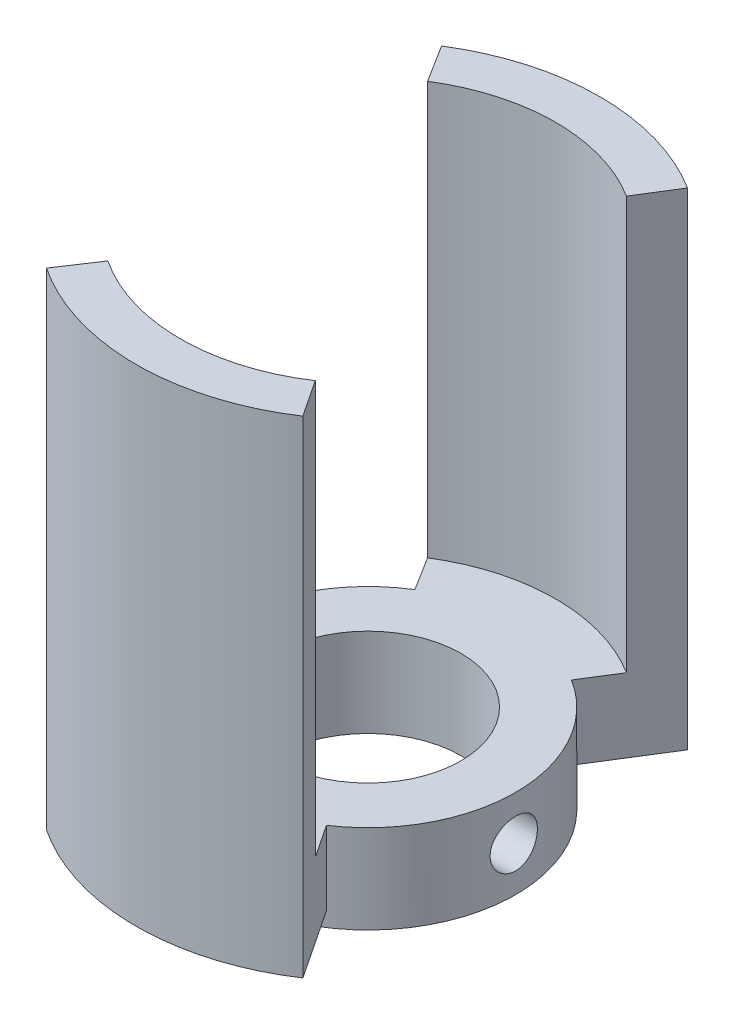
SolidWorks part; units mm, degrees
material "Plain Carbon Steel"
ref_plane "Front Plane" through (0, 0, 0) normal (0, 0, 1) x (1, 0, 0)
ref_plane "Top Plane" through (0, 0, 0) normal (0, 1, 0) x (1, 0, 0)
ref_plane "Right Plane" through (0, 0, 0) normal (1, 0, 0) x (0, 0, -1)
sketch "Sketch1" plane through (0, 0, 0) normal (0, 0, 1) x (1, 0, 0)
  line L0 (0, 5.8882) -> (0, -5.8882) construction
  line L7 (0, 0) -> (0, -3)
  line L9 (-5, -3) -> (0, -3)
  line L12 (-5, -3) -> (-5, 0)
  line L13 (-5, 0) -> (0, 0)
  dimension "D4" = 5
revolve "Revolve1" add sketch "Sketch1" angle 360 about L0
sketch "Sketch2" plane through (0, 0, 0) normal (0, 1, 0) x (1, 0, 0)
  circle A0 centre (0, 0) radius 3.15
  dimension "D1" = 6.3
extrude "Cut-Extrude1" cut sketch "Sketch2" against normal through all
ref_plane "Plane1" through (5, 0, 0) normal (1, 0, 0) x (0, 0, -1)
hole_wizard "M2x0.4 Tapped Hole2" positions "Sketch7" profile "Sketch8" tap size "M2x0.4" standard "ANSI Metric"
sketch "Sketch7" plane through (5, 0, 0) normal (1, 0, 0) x (0, 0, -1)
  line L0 (-5, 0) -> (5, 0) construction
  point P0 (0, -1.5)
  dimension "D1" = 1.5
sketch "Sketch8" plane through (5, -1.5, 0) normal (0, 1, 0) x (0, 0, -1)
  line L0 (0, 0) -> (0, 1.85)
  line L1 (0, 1.85) -> (0.8, 1.85)
  line L2 (0.8, 1.85) -> (0.8, 0)
  line L5 (0.8, 0) -> (0, 0)
  line L11 (0, -6.35) -> (0, 107.95) construction
  dimension "Thru Tap Drill Dia." = 1.6
  dimension "Thru Tap Drill Depth" = 1.85
cosmetic thread "Hole Thread1" parameters "D1"=2.1086, "D2"=2
sketch "Sketch9" plane through (0, 0, 0) normal (0, 1, 0) x (1, 0, 0)
  line L2 (-3.3663, 5.3843) -> (-4.1615, 6.6561)
  line L3 (3.3663, 5.3843) -> (4.1615, 6.6561)
  line L4 (3.5096, -5.292) -> (4.3387, -6.542)
  line L5 (-3.5096, -5.292) -> (-4.3387, -6.542)
  arc A3 (-3.5096, -5.292) -> (3.5096, -5.292) centre (0, 0) ccw
  arc A4 (3.3663, 5.3843) -> (-3.3663, 5.3843) centre (0, 0) ccw
  arc A5 (-4.3387, -6.542) -> (4.3387, -6.542) centre (0, 0) ccw
  arc A6 (4.1615, 6.6561) -> (-4.1615, 6.6561) centre (0, 0) ccw
  circle A7 centre (0, 0) radius 3.15 construction
  point P2 (0, 6.35)
  point P15 (0, -6.35)
  dimension "D1" = 12.7
  dimension "D2" = 1.5
  dimension "D3" = 3.5096
  dimension "D4" = 4.1615
extrude "Boss-Extrude1" add sketch "Sketch9" along normal blind 13.97 separate body
sketch "Sketch11" plane through (0, 0, 0) normal (0, -1, 0) x (1, 0, 0)
  line L0 (4.1615, -6.6561) -> (3.3663, -5.3843) construction
  line L1 (-3.3663, -5.3843) -> (-4.1615, -6.6561) construction
  line L2 (-4.3387, 6.542) -> (-3.5096, 5.292) construction
  line L3 (3.5096, 5.292) -> (4.3387, 6.542) construction
  line L4 (4.1615, -6.6561) -> (2.6506, -4.2396)
  line L5 (-2.6506, -4.2396) -> (-4.1615, -6.6561)
  line L6 (-4.3387, 6.542) -> (-2.7635, 4.1669)
  line L7 (2.7635, 4.1669) -> (4.3387, 6.542)
  arc A0 (-4.1615, -6.6561) -> (4.1615, -6.6561) centre (0, 0) ccw construction
  arc A2 (4.3387, 6.542) -> (-4.3387, 6.542) centre (0, 0) ccw construction
  arc A4 (-4.1615, -6.6561) -> (4.1615, -6.6561) centre (0, 0) ccw
  arc A6 (4.3387, 6.542) -> (-4.3387, 6.542) centre (0, 0) ccw
  circle A8 centre (0, 0) radius 5 construction
  arc A9 (-2.6506, -4.2396) -> (2.6506, -4.2396) centre (0, 0) ccw
  arc A10 (2.7635, 4.1669) -> (-2.7635, 4.1669) centre (0, 0) ccw
extrude "Boss-Extrude2" add sketch "Sketch11" along normal blind 2.5
